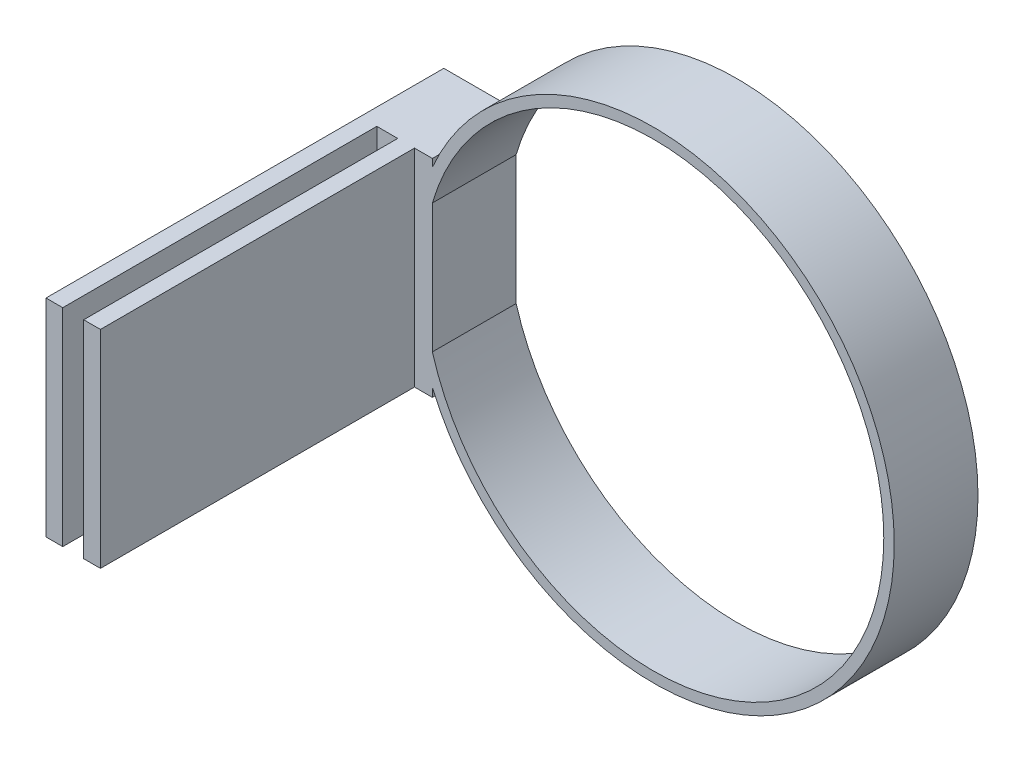
SolidWorks part; units mm, degrees
ref_plane "前基準面" through (0, 0, 0) normal (0, 0, 1) x (1, 0, 0)
ref_plane "上基準面" through (0, 0, 0) normal (0, 1, 0) x (1, 0, 0)
ref_plane "右基準面" through (0, 0, 0) normal (1, 0, 0) x (0, 0, -1)
sketch "草圖1" plane through (0, 0, 0) normal (0, 0, 1) x (1, 0, 0)
  line L1 (-33.4237, 19.7502) -> (-16.1547, 19.7502)
  line L2 (-33.4237, 19.7502) -> (-33.4237, -29.675)
  line L3 (-33.4237, -29.675) -> (-16.1547, -29.675)
  line L4 (-16.1547, 19.7502) -> (-16.1547, -29.675)
  circle A0 centre (36.6449, -4.8631) radius 55
  circle A1 centre (36.6449, -4.8631) radius 57.5
  dimension "D1" = 110
  dimension "D2" = 115
extrude "填料-伸長1" add sketch "草圖1" along normal blind 20 contours L4 A1 A0 | A1 L4 L1 L2 L3 | L4 A1 A0 | L4 A0
sketch "草圖2" plane through (0, 0, 20) normal (0, 0, 1) x (1, 0, 0)
  line L0 (-33.4237, -29.675) -> (-16.1547, -29.675) construction
  line L5 (-33.4237, 19.7502) -> (-29.4237, 19.7502)
  line L6 (-24.4237, 19.7502) -> (-20.4237, 19.7502)
  line L7 (-24.4237, 19.7502) -> (-24.4237, -29.675)
  line L8 (-24.4237, -29.675) -> (-20.4237, -29.675)
  line L9 (-20.4237, 19.7502) -> (-20.4237, -29.675)
  line L10 (-33.4237, 19.7502) -> (-33.4237, -29.675)
  line L11 (-33.4237, -29.675) -> (-29.4237, -29.675)
  line L12 (-29.4237, 19.7502) -> (-29.4237, -29.675)
  dimension "D1" = 4
  dimension "D2" = 4
  dimension "D3" = 5
extrude "填料-伸長2" add sketch "草圖2" along normal blind 75 contours L10 L5 L12 L11 | L7 L6 L9 L8
